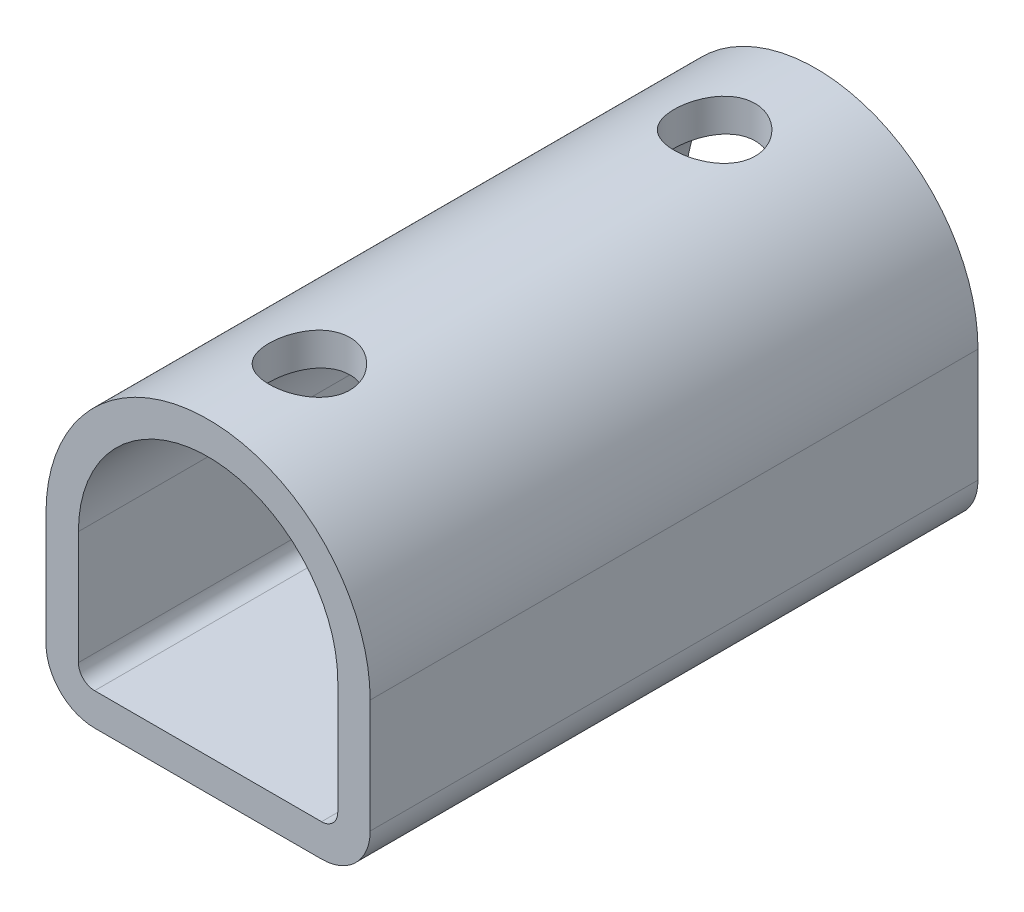
SolidWorks part; units mm, degrees
ref_plane "Plan de face" through (0, 0, 0) normal (0, 0, 1) x (1, 0, 0)
ref_plane "Plan de dessus" through (0, 0, 0) normal (0, 1, 0) x (1, 0, 0)
ref_plane "Plan de droite" through (0, 0, 0) normal (1, 0, 0) x (0, 0, -1)
sketch "Esquisse1" plane through (0, 0, 0) normal (0, 0, 1) x (1, 0, 0)
  line L0 (-20.6417, -0.5775) -> (-20.6417, 13.4225)
  line L1 (19.3583, 13.4225) -> (19.3583, -0.5775)
  line L2 (13.3583, -6.5775) -> (-14.6417, -6.5775)
  line L3 (13.3583, -2.5775) -> (-14.6417, -2.5775)
  line L4 (-16.6417, -0.5775) -> (-16.6417, 13.4225)
  line L5 (15.3583, 13.4225) -> (15.3583, -0.5775)
  arc A0 (-20.6417, 13.4225) -> (19.3583, 13.4225) centre (-0.6417, 13.4225) cw
  arc A1 (-20.6417, -0.5775) -> (-14.6417, -6.5775) centre (-14.6417, -0.5775) ccw
  arc A2 (19.3583, -0.5775) -> (13.3583, -6.5775) centre (13.3583, -0.5775) cw
  arc A3 (-16.6417, -0.5775) -> (-14.6417, -2.5775) centre (-14.6417, -0.5775) ccw
  arc A4 (-16.6417, 13.4225) -> (15.3583, 13.4225) centre (-0.6417, 13.4225) cw
  arc A5 (15.3583, -0.5775) -> (13.3583, -2.5775) centre (13.3583, -0.5775) cw
  point P7 (-20.6417, -6.5775)
  dimension "D2" = 20
  dimension "D3" = 6
  dimension "D4" = 6
  dimension "D1" = 20
  dimension "D5" = 4
extrude "Boss.-Extru.1" add sketch "Esquisse1" along normal blind 75
sketch "Esquisse2" plane through (0, 0, 0) normal (0, 1, 0) x (1, 0, 0)
  line L3 (-20.6417, -75) -> (19.3583, -75) construction
  line L6 (19.3583, 0) -> (-20.6417, 0) construction
  line L7 (-0.6417, 0) -> (-0.6417, -75) construction
  circle A0 centre (-0.6417, -12.5) radius 5
  circle A1 centre (-0.6417, -62.5) radius 5
  dimension "D2" = 10
  dimension "D3" = 10
  dimension "D4" = 12.5
  dimension "D1" = 50
  dimension "D5" = 12.5
extrude "Enlèv. mat.-Extru.1" cut sketch "Esquisse2" along normal blind 75
